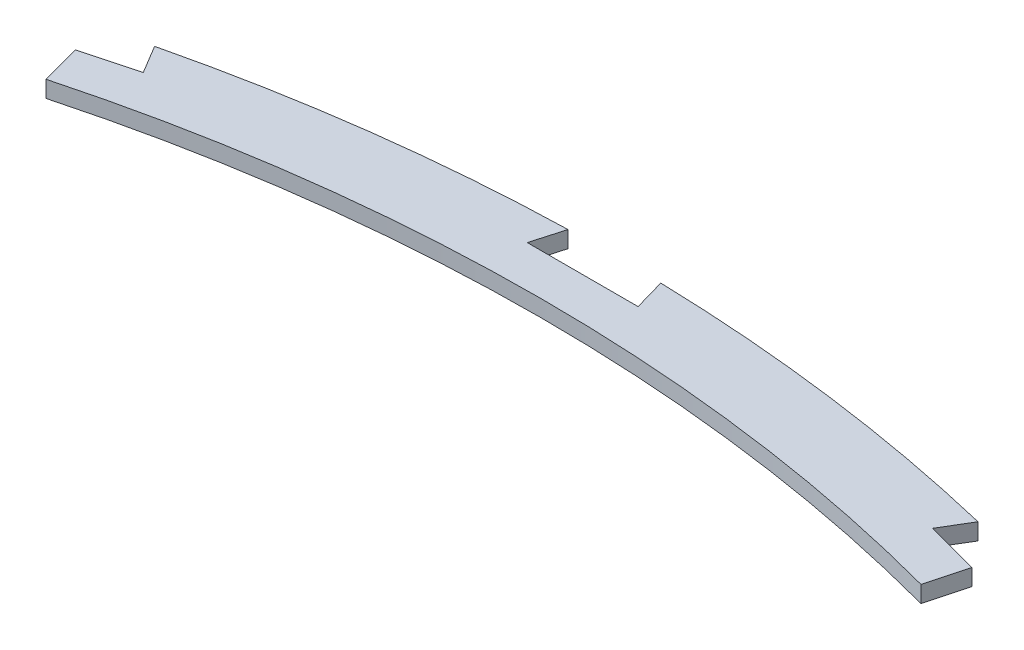
SolidWorks part; units mm, degrees
ref_plane "Front Plane" through (0, 0, 0) normal (0, 0, 1) x (1, 0, 0)
ref_plane "Top Plane" through (0, 0, 0) normal (0, 1, 0) x (1, 0, 0)
ref_plane "Right Plane" through (0, 0, 0) normal (1, 0, 0) x (0, 0, -1)
sketch "Sketch1" plane through (0, 0, 0) normal (0, 1, 0) x (1, 0, 0)
  line L0 (0, 0) -> (-280.8187, 1048.0295)
  line L1 (-280.8187, 1085) -> (280.8187, 1085) construction
  line L2 (-280.8187, 1085) -> (-280.8187, 785) construction
  line L3 (-280.8187, 785) -> (280.8187, 785) construction
  line L4 (280.8187, 1085) -> (280.8187, 785) construction
  line L5 (0, 0) -> (280.8187, 1048.0295)
  line L6 (0, 1020) -> (0, 0) construction
  line L7 (-30, 937.5) -> (30, 937.5)
  line L8 (30, 937.5) -> (25.0942, 954.6702)
  line L9 (955, 0) -> (1000, 0) construction
  line L10 (1000, 0) -> (1045, 0) construction
  line L11 (-30, 937.5) -> (-25.0942, 954.6702)
  line L12 (-242.6429, 905.5555) -> (-213.6651, 913.32)
  line L13 (-213.6651, 913.32) -> (-222.8477, 928.6355)
  line L14 (242.6429, 905.5555) -> (213.6651, 913.32)
  line L15 (213.6651, 913.32) -> (222.8477, 928.6355)
  circle A0 centre (0, 0) radius 1085
  circle A1 centre (0, 0) radius 1045
  circle A2 centre (0, 0) radius 955
  circle A3 centre (0, 0) radius 915
  circle A6 centre (0, 0) radius 1065 construction
  circle A7 centre (0, 0) radius 935 construction
  circle A12 centre (0, 0) radius 1032.5 construction
  circle A15 centre (0, 0) radius 1000 construction
  point P12 (0, 785)
  point P17 (25, 955)
  point P25 (0, 937.5)
  point P27 (-223.024, 928.9296)
  dimension "D8" = 2000
  dimension "D1" = 300
  dimension "D3" = 40
  dimension "D4" = 40
  dimension "D5" = 20
  dimension "D6" = 20
  dimension "D7" = 170
  dimension "D2" = 15
  dimension "D13" = 15
  dimension "D14" = 12.5
  dimension "D9" = 30
  dimension "D10" = 25
  dimension "D11" = 17.5
  dimension "D12" = 937.5
  dimension "D15" = 30
  dimension "D16" = 17.5
  dimension "D17" = 25
  dimension "D18" = 937.5
extrude "Boss-Extrude1" add sketch "Sketch1" along normal blind 9 contours A3 L5 A2 L8 L7 L11 L0
equation "\"D12@Sketch1\"=1910/2-17.5"
equation "\"D18@Sketch1\"=1910/2-17.5"
